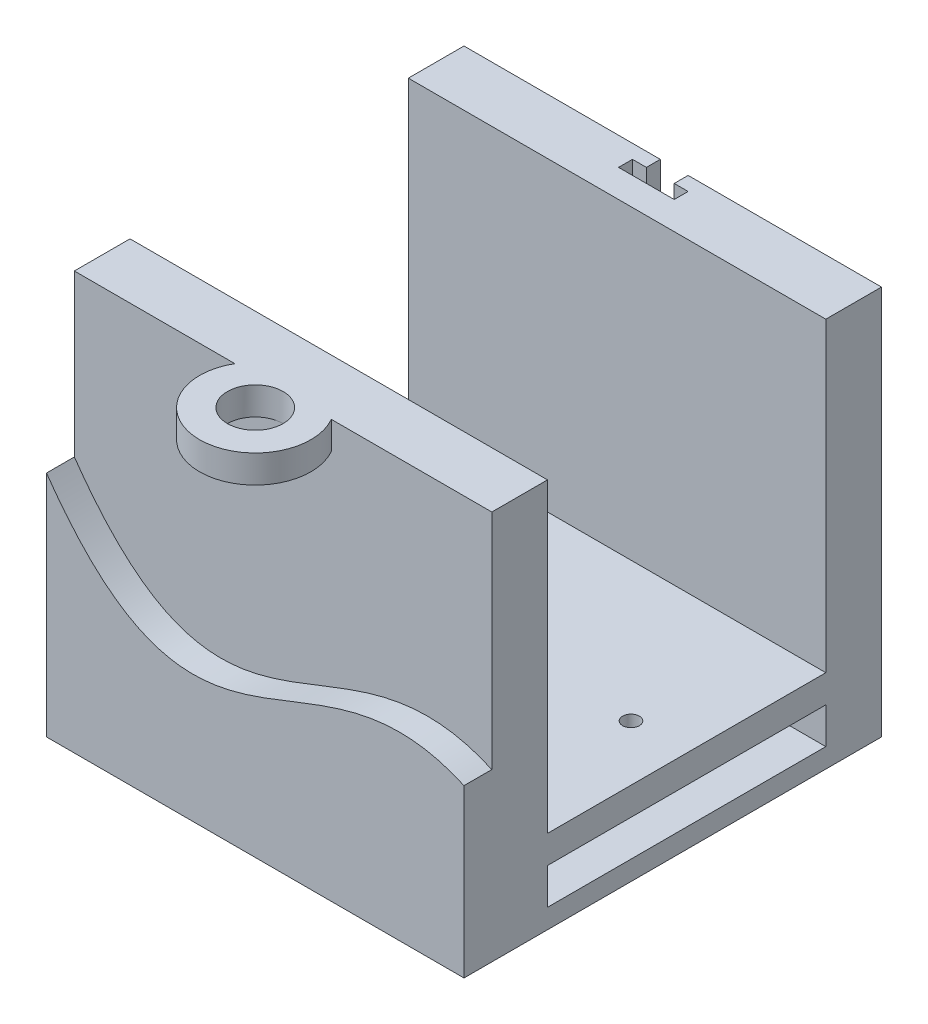
SolidWorks part; units mm, degrees
ref_plane "前基準面" through (0, 0, 0) normal (0, 0, 1) x (1, 0, 0)
ref_plane "上基準面" through (0, 0, 0) normal (0, 1, 0) x (1, 0, 0)
ref_plane "右基準面" through (0, 0, 0) normal (1, 0, 0) x (0, 0, -1)
sketch "草圖2" plane through (0, 0, 0) normal (0, 1, 0) x (1, 0, 0)
  line L1 (-59.1429, 35.7857) -> (90.8571, 35.7857)
  line L2 (-59.1429, 35.7857) -> (-59.1429, -104.2143)
  line L3 (-59.1429, -104.2143) -> (90.8571, -104.2143)
  line L4 (90.8571, 35.7857) -> (90.8571, -104.2143)
  dimension "D1" = 150
  dimension "D2" = 140
extrude "填料-伸長1" add sketch "草圖2" along normal blind 140
sketch "草圖3" plane through (0, 140, 0) normal (0, 1, 0) x (1, 0, 0)
  line L0 (90.8571, 35.7857) -> (-59.1429, 35.7857) construction
  line L1 (-59.1429, 15.7857) -> (90.8571, 15.7857)
  line L2 (-59.1429, 15.7857) -> (-59.1429, -84.2143)
  line L3 (-59.1429, -84.2143) -> (90.8571, -84.2143)
  line L4 (90.8571, 15.7857) -> (90.8571, -84.2143)
  line L5 (-59.1429, -104.2143) -> (90.8571, -104.2143) construction
  line L6 (-59.1429, 35.7857) -> (-59.1429, -104.2143) construction
  line L7 (90.8571, -104.2143) -> (90.8571, 35.7857) construction
  dimension "D1" = 20
  dimension "D2" = 20
  dimension "D3" = 0
  dimension "D4" = 0
extrude "除料-伸長1" cut sketch "草圖3" against normal blind 110
sketch "草圖4" plane through (90.8571, 0, 0) normal (1, 0, 0) x (0, 0, -1)
  line L0 (-104.2143, 140) -> (-104.2143, 0) construction
  line L1 (-84.2143, 20) -> (15.7857, 20)
  line L2 (-84.2143, 20) -> (-84.2143, 7)
  line L3 (-84.2143, 7) -> (15.7857, 7)
  line L4 (15.7857, 20) -> (15.7857, 7)
  line L5 (-84.2143, 30) -> (15.7857, 30) construction
  line L6 (-104.2143, 0) -> (35.7857, 0) construction
  dimension "D1" = 100
  dimension "D2" = 20
  dimension "D3" = 10
  dimension "D4" = 7
extrude "除料-伸長2" cut sketch "草圖4" against normal through all
sketch "草圖5" plane through (0, 30, 0) normal (0, 1, 0) x (1, 0, 0)
  line L0 (90.8571, -34.2143) -> (70.8571, -34.2143) construction
  line L1 (90.8571, -84.2143) -> (90.8571, 15.7857) construction
  circle A0 centre (70.8571, -34.2143) radius 3
  dimension "D2" = 6
  dimension "D1" = 20
extrude "除料-伸長3" cut sketch "草圖5" against normal blind 50
sketch "草圖6" plane through (0, 30, 0) normal (0, 1, 0) x (1, 0, 0)
  line L0 (-59.1429, -34.2143) -> (-29.1429, -34.2143) construction
  line L1 (-59.1429, 15.7857) -> (-59.1429, -84.2143) construction
  circle A0 centre (-29.1429, -34.2143) radius 3
  dimension "D1" = 6
extrude "除料-伸長4" cut sketch "草圖6" against normal through all
sketch "草圖7" plane through (0, 140, 0) normal (0, 1, 0) x (1, 0, 0)
  line L0 (15.8571, -104.2143) -> (15.8571, -124.2143) construction
  line L1 (-59.1429, -104.2143) -> (90.8571, -104.2143) construction
  circle A0 centre (15.8571, -114.2143) radius 10
  dimension "D2" = 20
  dimension "D1" = 20
extrude "伸長-薄件1" add sketch "草圖7" against normal blind 10 thin
sketch "草圖8" plane through (0, 140, 0) normal (0, 1, 0) x (1, 0, 0)
  line L0 (15.8571, -964.2143) -> (15.8571, 49035.7857) construction
  line L1 (90.8571, 35.7857) -> (-59.1429, 35.7857) construction
  line L3 (21.3829, 35.7857) -> (11.3829, 35.7857)
  line L4 (21.3829, 35.7857) -> (21.3829, 25.7857)
  line L5 (21.3829, 25.7857) -> (11.3829, 25.7857)
  line L6 (11.3829, 35.7857) -> (11.3829, 25.7857)
  point P5 (15.8571, 35.7857)
  dimension "D1" = 10
  dimension "D2" = 10
extrude "除料-伸長5" cut sketch "草圖8" against normal blind 120
sketch "草圖10" plane through (0, 140, 0) normal (0, 1, 0) x (1, 0, 0)
  line L0 (21.3829, 25.7857) -> (21.3829, 35.7857) construction
  line L1 (6.3829, 25.7857) -> (26.3829, 25.7857)
  line L2 (6.3829, 25.7857) -> (6.3829, 30.7857)
  line L3 (6.3829, 30.7857) -> (26.3829, 30.7857)
  line L4 (26.3829, 25.7857) -> (26.3829, 30.7857)
  line L5 (11.3829, 35.7857) -> (11.3829, 25.7857) construction
  dimension "D1" = 5
  dimension "D2" = 5
  dimension "D3" = 5
extrude "除料-伸長7" cut sketch "草圖10" against normal blind 120
sketch "草圖11" plane through (0, 0, 104.2143) normal (0, 0, 1) x (1, 0, 0)
  line L0 (-59.1429, 140) -> (-59.1429, 0) construction
  line L1 (90.8571, 140) -> (90.8571, 0) construction
  line L2 (-59.1429, 82.1361) -> (-59.1429, 0)
  line L3 (-59.1429, 0) -> (90.8571, 0)
  line L4 (90.8571, 0) -> (90.8571, 59.8589)
  spline S0 degree 3 poles (-59.1429, 82.1361) (-2.2607, 0.5745) (33.52, 85.66) (90.8571, 59.8589) knots 0 0 0 0 1 1 1 1
extrude "填料-伸長2" add sketch "草圖11" along normal blind 10
